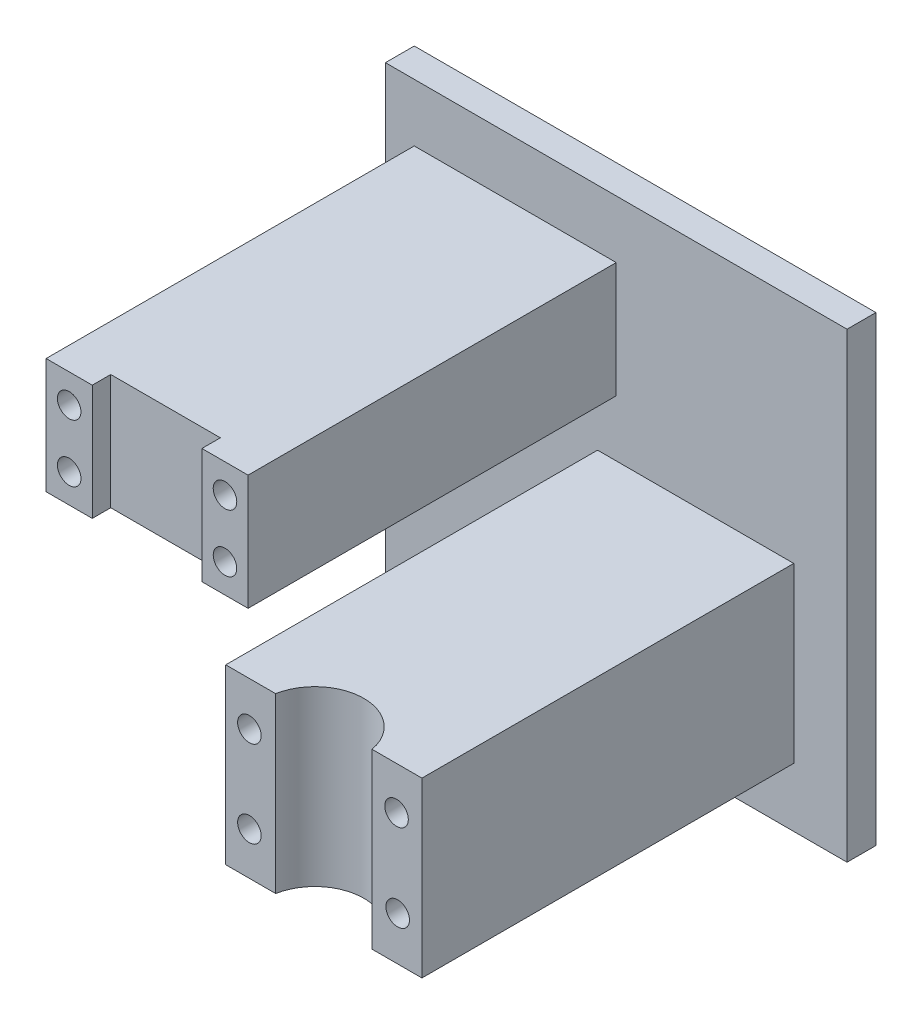
SolidWorks part; units mm, degrees
ref_plane "Front Plane" through (0, 0, 0) normal (0, 0, 1) x (1, 0, 0)
ref_plane "Top Plane" through (0, 0, 0) normal (0, 1, 0) x (1, 0, 0)
ref_plane "Right Plane" through (0, 0, 0) normal (1, 0, 0) x (0, 0, -1)
sketch "Sketch1" plane through (0, 0, 0) normal (0, 0, 1) x (1, 0, 0)
  line L1 (0, 0) -> (-101.6, 0)
  line L2 (0, 0) -> (0, 101.6)
  line L3 (0, 101.6) -> (-101.6, 101.6)
  line L4 (-101.6, 0) -> (-101.6, 101.6)
  dimension "D1" = 101.6
  dimension "D2" = 101.6
extrude "Boss-Extrude1" add sketch "Sketch1" along normal blind 6.35
sketch "Sketch2" plane through (0, 0, 6.35) normal (0, 0, 1) x (1, 0, 0)
  line L1 (-95.25, 88.9) -> (-50.8, 88.9)
  line L2 (-95.25, 88.9) -> (-95.25, 63.5)
  line L3 (-95.25, 63.5) -> (-50.8, 63.5)
  line L4 (-50.8, 88.9) -> (-50.8, 63.5)
  point P4 (-95.25, 76.2)
  dimension "D1" = 25.4
  dimension "D2" = 44.45
  dimension "D3" = 50.8
  dimension "D4" = 25.4
extrude "Boss-Extrude3" add sketch "Sketch2" along normal blind 101.6
sketch "Sketch4" plane through (0, 63.5, 0) normal (0, -1, 0) x (1, 0, 0)
  line L1 (-85.09, 95.25) -> (-60.96, 95.25)
  line L2 (-85.09, 95.25) -> (-85.09, 83.312)
  line L3 (-85.09, 83.312) -> (-60.96, 83.312)
  line L4 (-60.96, 95.25) -> (-60.96, 83.312)
  line L5 (-95.25, 107.95) -> (-50.8, 107.95) construction
  dimension "D1" = 11.938
  dimension "D2" = 24.13
  dimension "D3" = 10.16
  dimension "D4" = 12.7
extrude "Cut-Extrude1" cut sketch "Sketch4" against normal blind 101.6
sketch "Sketch5" plane through (0, 0, 6.35) normal (0, 0, 1) x (1, 0, 0)
  line L1 (-54.906, 12.9915) -> (-11.726, 12.9915)
  line L2 (-54.906, 12.9915) -> (-54.906, 51.0915)
  line L3 (-54.906, 51.0915) -> (-11.726, 51.0915)
  line L4 (-11.726, 12.9915) -> (-11.726, 51.0915)
  dimension "D1" = 43.18
  dimension "D2" = 38.1
extrude "Boss-Extrude4" add sketch "Sketch5" along normal blind 101.6
sketch "Sketch6" plane through (0, 51.0915, 0) normal (0, 1, 0) x (1, 0, 0)
  circle A0 centre (-33.316, -90.17) radius 10.795
  dimension "D1" = 17.78
  dimension "D2" = 21.59
extrude "Cut-Extrude2" cut sketch "Sketch6" against normal through all
sketch "Sketch7" plane through (0, 51.0915, 0) normal (0, 1, 0) x (1, 0, 0)
  line L0 (-54.906, -107.95) -> (-54.906, -6.35) construction
  line L1 (-11.726, -107.95) -> (-54.906, -107.95)
  line L2 (-11.726, -107.95) -> (-11.726, -90.0901)
  line L3 (-11.726, -90.0901) -> (-54.906, -90.0901)
  line L4 (-54.906, -107.95) -> (-54.906, -90.0901)
extrude "Cut-Extrude3" cut sketch "Sketch7" against normal through all
sketch "Sketch8" plane through (0, 88.9, 0) normal (0, 1, 0) x (1, 0, 0)
  line L0 (-95.25, -107.95) -> (-95.25, -6.35) construction
  line L1 (-50.8, -107.95) -> (-95.25, -107.95)
  line L2 (-50.8, -107.95) -> (-50.8, -89.281)
  line L3 (-50.8, -89.281) -> (-95.25, -89.281)
  line L4 (-95.25, -107.95) -> (-95.25, -89.281)
  dimension "D1" = 18.669
extrude "Cut-Extrude4" cut sketch "Sketch8" against normal up to next
hole_wizard "#6 (0.204) Diameter Hole1" positions "Sketch10" profile "Sketch12" hole size "#6" standard "ANSI Inch"
sketch "Sketch10" plane through (0, 0, 90.0901) normal (0, 0, 1) x (1, 0, 0)
  point P0 (-17.0603, 22.6435)
  point P2 (-17.314, 41.6935)
  point P4 (-49.6987, 41.4395)
  point P6 (-49.6987, 22.3895)
  dimension "D1" = 5.461
  dimension "D2" = 5.588
  dimension "D3" = 5.588
  dimension "D4" = 5.588
  dimension "D5" = 19.05
  dimension "D6" = 9.652
  dimension "D7" = 19.05
  dimension "D8" = 9.652
sketch "Sketch12" plane through (-17.0603, 22.6435, 90.0901) normal (1, 0, 0) x (0, -1, 0)
  line L0 (0, 0) -> (0, 14.2567)
  line L1 (0, 14.2567) -> (2.5908, 12.7)
  line L2 (2.5908, 12.7) -> (2.5908, 0)
  line L5 (2.5908, 0) -> (0, 0)
  line L10 (0, 14.2567) -> (-2.5908, 12.7) construction
  line L11 (0, -6.35) -> (0, 107.95) construction
  dimension "Hole Dia." = 5.1816
  dimension "Hole Depth" = 12.7
  dimension "Drill Angle" = 118
hole_wizard "#6 (0.204) Diameter Hole2" positions "Sketch15" profile "Sketch16" hole size "#6" standard "ANSI Inch"
sketch "Sketch15" plane through (0, 0, 89.281) normal (0, 0, 1) x (1, 0, 0)
  point P0 (-55.88, 82.55)
  point P2 (-55.88, 69.85)
  point P4 (-90.17, 82.55)
  point P6 (-90.17, 69.85)
  dimension "D1" = 5.08
  dimension "D2" = 5.08
  dimension "D3" = 5.08
  dimension "D4" = 5.08
  dimension "D5" = 12.7
  dimension "D6" = 6.35
  dimension "D7" = 12.7
  dimension "D8" = 6.35
sketch "Sketch16" plane through (-55.88, 82.55, 89.281) normal (1, 0, 0) x (0, -1, 0)
  line L0 (0, 0) -> (0, 14.2567)
  line L1 (0, 14.2567) -> (2.5908, 12.7)
  line L2 (2.5908, 12.7) -> (2.5908, 0)
  line L5 (2.5908, 0) -> (0, 0)
  line L10 (0, 14.2567) -> (-2.5908, 12.7) construction
  line L11 (0, -6.35) -> (0, 107.95) construction
  dimension "Hole Dia." = 5.1816
  dimension "Hole Depth" = 12.7
  dimension "Drill Angle" = 118
sketch "Sketch17" plane through (0, 12.9915, 0) normal (0, -1, 0) x (1, 0, 0)
  line L0 (-11.726, 90.0901) -> (-11.726, 6.35) construction
  line L1 (-54.906, 90.0901) -> (-11.726, 90.0901)
  line L2 (-54.906, 90.0901) -> (-54.906, 88.1851)
  line L3 (-54.906, 88.1851) -> (-11.726, 88.1851)
  line L4 (-11.726, 90.0901) -> (-11.726, 88.1851)
  dimension "D1" = 1.905
extrude "Cut-Extrude5" cut sketch "Sketch17" against normal up to next
sketch "Sketch18" plane through (0, 88.9, 0) normal (0, 1, 0) x (1, 0, 0)
  line L0 (-95.25, -89.281) -> (-95.25, -6.35) construction
  line L1 (-50.8, -89.281) -> (-95.25, -89.281)
  line L2 (-50.8, -89.281) -> (-50.8, -87.376)
  line L3 (-50.8, -87.376) -> (-95.25, -87.376)
  line L4 (-95.25, -89.281) -> (-95.25, -87.376)
  dimension "D1" = 1.905
extrude "Cut-Extrude6" cut sketch "Sketch18" against normal up to next
